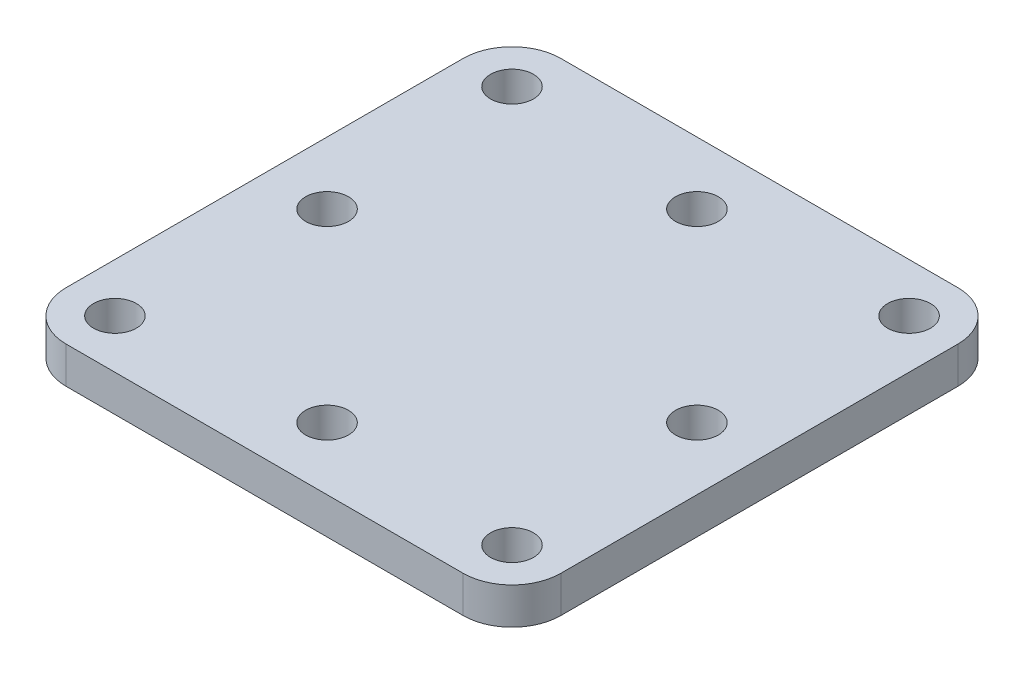
SolidWorks part; units mm, degrees
ref_plane "前视基准面" through (0, 0, 0) normal (0, 0, 1) x (1, 0, 0)
ref_plane "上视基准面" through (0, 0, 0) normal (0, 1, 0) x (1, 0, 0)
ref_plane "右视基准面" through (0, 0, 0) normal (1, 0, 0) x (0, 0, -1)
sketch "Sketch1" plane through (0, 0, 0) normal (0, 1, 0) x (1, 0, 0)
  circle A0 centre (0, 0) radius 11.9
  circle A1 centre (0, 0) radius 9.9
  dimension "D1" = 23.8
  dimension "D2" = 19.8
extrude "Boss-Extrude3" add sketch "Sketch1" along normal blind 15 contours A1 | A0
sketch "Sketch4" plane through (0, 0, 0) normal (0, -1, 0) x (1, 0, 0)
  circle A0 centre (0, 0) radius 9.9
extrude "Boss-Extrude4" add sketch "Sketch4" against normal blind 5.1
sketch "Sketch7" plane through (0, 0, 0) normal (1, 0, 0) x (0, 0, -1)
  line L0 (0, 15) -> (0, -4.8)
  arc A0 (0, -4.8) -> (0, 15) centre (0, 5.1) ccw
  dimension "D2" = 9.9
  dimension "D1" = 5.1
revolve "Cut-Revolve2" cut sketch "Sketch7" angle 360 about L0
sketch "Sketch12" plane through (0, 15, 0) normal (0, 1, 0) x (1, 0, 0)
  circle A0 centre (0, 0) radius 19
  circle A1 centre (0, 0) radius 11.9
  dimension "D1" = 38
extrude "Boss-Extrude8" add sketch "Sketch12" against normal blind 3
sketch "Sketch14" plane through (0, 15, 0) normal (0, 1, 0) x (1, 0, 0)
  line L0 (0, 0) -> (0, 22.9912) construction
  line L1 (0, 0) -> (27.8368, 0) construction
  line L2 (0, 0) -> (-27.3663, 0) construction
  line L3 (0, 0) -> (0, -24.0336) construction
  circle A0 centre (0, 15.15) radius 1.755
  circle A1 centre (-15.15, 0) radius 1.755
  circle A2 centre (0, -15.15) radius 1.755
  circle A3 centre (15.15, 0) radius 1.755
  dimension "D1" = 3.51
  dimension "D2" = 3.51
  dimension "D3" = 3.51
  dimension "D4" = 3.51
  dimension "D5" = 15.15
  dimension "D6" = 15.15
  dimension "D7" = 15.15
  dimension "D8" = 15.15
extrude "Cut-Extrude4" cut sketch "Sketch14" against normal blind 3
sketch "Sketch15" plane through (0, 0, 0) normal (1, 0, 0) x (0, 0, -1)
  line L1 (-19, 12) -> (19, 12)
  line L2 (-19, 12) -> (-19, -4.08)
  line L3 (-19, -4.08) -> (19, -4.08)
  line L4 (19, 12) -> (19, -4.08)
extrude "Cut-Extrude5" cut sketch "Sketch15" against normal blind 20 and the other way blind 25
sketch "Sketch16" plane through (0, 15, 0) normal (0, 1, 0) x (1, 0, 0)
  circle A0 centre (0, 0) radius 9.9
extrude "Boss-Extrude9" add sketch "Sketch16" against normal blind 3
sketch "Sketch17" plane through (0, 15, 0) normal (0, 1, 0) x (1, 0, 0)
  line L0 (-20, 20) -> (20, -20) construction
  line L1 (-20, 20) -> (20, 20)
  line L2 (-20, 20) -> (-20, -20)
  line L3 (-20, -20) -> (20, -20)
  line L4 (20, 20) -> (20, -20)
  line L5 (20, 20) -> (-20, -20) construction
  circle A0 centre (0, 0) radius 19
  dimension "D1" = 20
  dimension "D2" = 40
  dimension "D3" = 20
  dimension "D4" = 40
extrude "Boss-Extrude10" add sketch "Sketch17" against normal blind 3
sketch "Sketch20" plane through (0, 15, 0) normal (0, 1, 0) x (1, 0, 0)
  line L1 (-30, 30) -> (30, 30)
  line L2 (-30, 30) -> (-30, -30)
  line L3 (-30, -30) -> (30, -30)
  line L4 (30, 30) -> (30, -30)
  line L5 (-20, 20) -> (20, 20)
  line L6 (-20, 20) -> (-20, -20)
  line L7 (-20, -20) -> (20, -20)
  line L8 (20, 20) -> (20, -20)
  point P13 (9.4218, 24.1573)
  dimension "D1" = 30
  dimension "D2" = 30
  dimension "D3" = 30
  dimension "D4" = 30
extrude "Boss-Extrude11" add sketch "Sketch20" against normal blind 3
sketch "Sketch21" plane through (0, 15, 0) normal (0, 1, 0) x (1, 0, 0)
  line L0 (0, 0) -> (25.3354, 25.3354) construction
  line L1 (0, 0) -> (-24.4377, -24.4377) construction
  line L2 (0, 0) -> (26.151, -26.151) construction
  line L3 (0, 0) -> (-23.3223, 23.3223) construction
  line L4 (-20.2635, 16.2635) -> (-20.2635, -17.8436)
  line L5 (-16.2635, 20.2635) -> (16.2635, 20.2635)
  line L6 (20.2635, 16.2635) -> (20.2635, -16.2635)
  line L7 (-16.2635, -20.2635) -> (16.2635, -20.2635)
  circle A0 centre (0, 0) radius 27
  circle A1 centre (0, 0) radius 19
  circle A2 centre (-16.2635, 16.2635) radius 4
  circle A3 centre (16.2635, -16.2635) radius 4
  circle A4 centre (-16.2635, -16.2635) radius 4
  circle A5 centre (16.2635, 16.2635) radius 4
  circle A6 centre (-16.2635, 16.2635) radius 1.755
  circle A7 centre (16.2635, 16.2635) radius 1.755
  circle A8 centre (16.2635, -16.2635) radius 1.755
  circle A9 centre (-16.2635, -16.2635) radius 1.755
  dimension "D5" = 23
  dimension "D6" = 8
  dimension "D1" = 54
  dimension "D2" = 38
  dimension "D4" = 8
  dimension "D8" = 8
  dimension "D10" = 8
  dimension "D11" = 3.51
  dimension "D12" = 3.51
  dimension "D13" = 3.51
  dimension "D14" = 3.51
  dimension "D3" = 23
  dimension "D7" = 23
  dimension "D9" = 23
extrude "Cut-Extrude7" cut sketch "Sketch21" against normal blind 3 contours A6 | A9 | A7 | A8
sketch "Sketch23" plane through (0, 15, 0) normal (0, 1, 0) x (1, 0, 0)
  line L0 (-16.2635, 16.2635) -> (-21.8925, 16.2635) construction
  line L1 (-16.2635, 16.2635) -> (-16.2635, 21.8596) construction
  line L2 (16.2635, 16.2635) -> (21.4673, 16.2635) construction
  line L3 (16.2635, 16.2635) -> (16.2635, 20.813) construction
  line L4 (16.2635, -16.2635) -> (22.3518, -16.2635) construction
  line L5 (16.2635, -16.2635) -> (16.2635, -21.2937) construction
  line L6 (-16.2635, -16.2635) -> (-21.8925, -16.2635) construction
  line L7 (-16.2635, -16.2635) -> (-16.2635, -23.6212) construction
  line L8 (-20.2635, -16.2635) -> (-20.2635, 16.2635)
  line L9 (-16.2635, 20.2635) -> (16.2635, 20.2635)
  line L10 (20.2635, 16.2635) -> (20.2635, -16.2635)
  line L11 (16.2635, -20.2635) -> (-16.2635, -20.2635)
  line L13 (-30, 30) -> (30, 30)
  line L14 (-30, 30) -> (-30, -30)
  line L15 (-30, -30) -> (30, -30)
  line L16 (30, 30) -> (30, -30)
  arc A0 (-20.2635, 16.2635) -> (-16.2635, 20.2635) centre (-16.2635, 16.2635) cw
  arc A1 (20.2635, 16.2635) -> (16.2635, 20.2635) centre (16.2635, 16.2635) ccw
  arc A2 (20.2635, -16.2635) -> (16.2635, -20.2635) centre (16.2635, -16.2635) cw
  arc A3 (-20.2635, -16.2635) -> (-16.2635, -20.2635) centre (-16.2635, -16.2635) ccw
  dimension "D1" = 4
  dimension "D2" = 4
  dimension "D3" = 4
  dimension "D4" = 4
extrude "Cut-Extrude9" cut sketch "Sketch23" against normal blind 3
